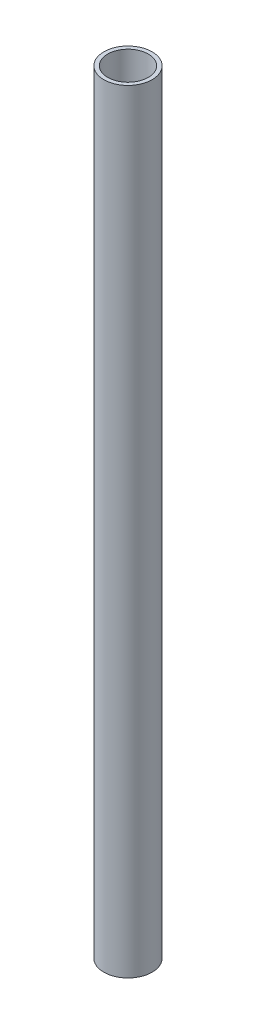
SolidWorks part; units mm, degrees
ref_plane "Alzado" through (0, 0, 0) normal (0, 0, 1) x (1, 0, 0)
ref_plane "Planta" through (0, 0, 0) normal (0, 1, 0) x (1, 0, 0)
ref_plane "Vista lateral" through (0, 0, 0) normal (1, 0, 0) x (0, 0, -1)
sketch "Croquis1" plane through (0, 0, 0) normal (0, 1, 0) x (1, 0, 0)
  circle A0 centre (0, 0) radius 12.5
  circle A1 centre (0, 0) radius 10.5
  dimension "D1" = 25
  dimension "D2" = 2
extrude "Saliente-Extruir1" add sketch "Croquis1" along normal blind 400
